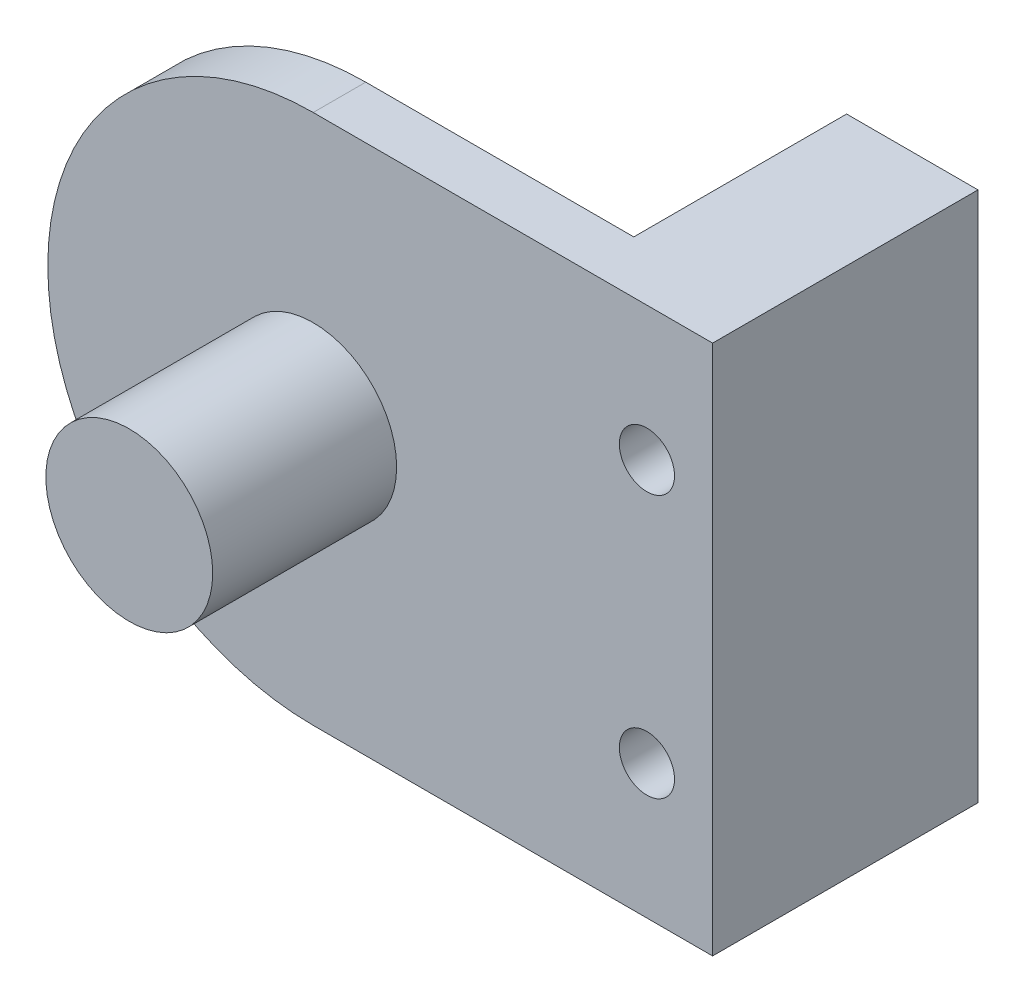
SolidWorks part; units mm, degrees
material "ABS"
ref_plane "Front" through (0, 0, 0) normal (0, 0, 1) x (1, 0, 0)
ref_plane "Top" through (0, 0, 0) normal (0, 1, 0) x (1, 0, 0)
ref_plane "Right" through (0, 0, 0) normal (1, 0, 0) x (0, 0, -1)
sketch "Esquisse1" plane through (0, 0, 0) normal (0, 0, 1) x (1, 0, 0)
  line L1 (-2.5, 10.1) -> (2.5, 10.1)
  line L2 (-2.5, 10.1) -> (-2.5, -10.1)
  line L3 (-2.5, -10.1) -> (2.5, -10.1)
  line L4 (2.5, 10.1) -> (2.5, -10.1)
  line L5 (-2.5, 10.1) -> (2.5, -10.1) construction
  line L6 (-2.5, -10.1) -> (2.5, 10.1) construction
  point P0 (0, 0)
  dimension "D1" = 5
  dimension "D2" = 20.2
extrude "Boss.-Extru.1" add sketch "Esquisse1" along normal blind 8.1
sketch "Esquisse2" plane through (0, 0, 8.1) normal (0, 0, 1) x (1, 0, 0)
  line L0 (-2.5, -10.1) -> (2.5, -10.1) construction
  line L1 (2.5, 10.1) -> (-12.7, 10.1)
  line L2 (2.5, 10.1) -> (2.5, -10.1)
  line L3 (2.5, -10.1) -> (-12.7, -10.1)
  arc A0 (-12.7, 10.1) -> (-12.7, -10.1) centre (-12.7, 0) ccw
  dimension "D1" = 15.2
extrude "Boss.-Extru.2" add sketch "Esquisse2" along normal blind 2
sketch "Esquisse3" plane through (0, 0, 10.1) normal (0, 0, 1) x (1, 0, 0)
  circle A0 centre (-12.7, 0) radius 3.175
  arc A1 (-12.7, 10.1) -> (-12.7, -10.1) centre (-12.7, 0) ccw construction
  dimension "D1" = 6.35
extrude "Boss.-Extru.3" add sketch "Esquisse3" along normal blind 7
sketch "Esquisse4" plane through (0, 0, 0) normal (0, 0, -1) x (-1, 0, 0)
  line L0 (-2.5, 10.1) -> (2.5, 10.1) construction
  line L1 (-2.5, -10.1) -> (-2.5, 10.1) construction
  circle A0 centre (0, 5) radius 1.05
  circle A2 centre (0, -5) radius 1.05
  dimension "D1" = 2
  dimension "D2" = 5.1
  dimension "D3" = 2.1
  dimension "D4" = 2.5
extrude "Enlèv. mat.-Extru.1" cut sketch "Esquisse4" against normal through all
